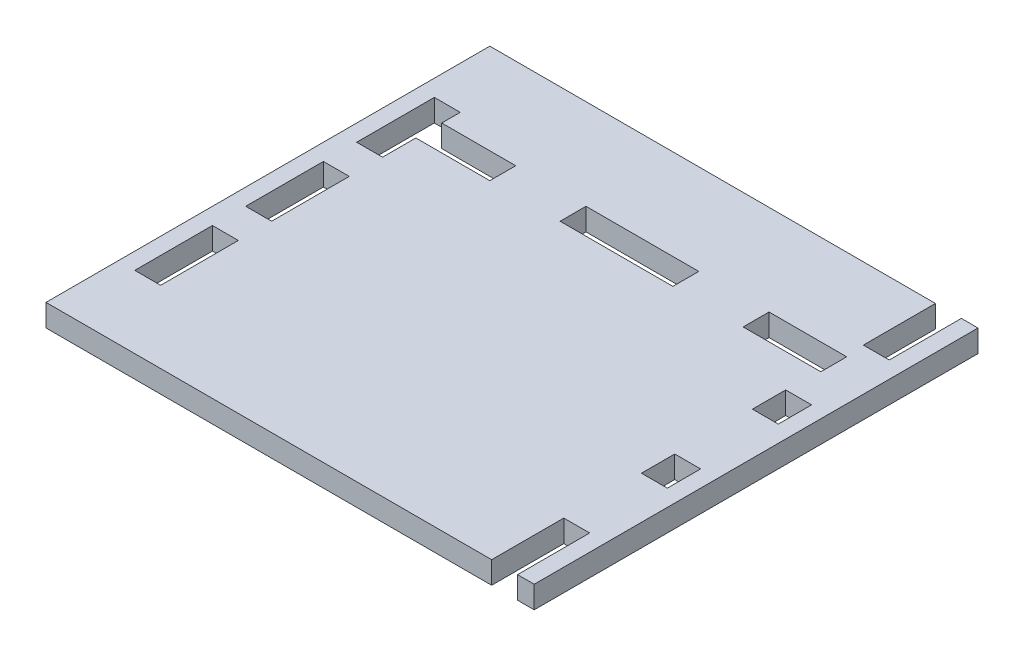
SolidWorks part; units mm, degrees
ref_plane "Спереди" through (0, 0, 0) normal (0, 0, 1) x (1, 0, 0)
ref_plane "Сверху" through (0, 0, 0) normal (0, 1, 0) x (1, 0, 0)
ref_plane "Справа" through (0, 0, 0) normal (1, 0, 0) x (0, 0, -1)
sketch "Эскиз1" plane through (0, 0, 0) normal (0, 1, 0) x (1, 0, 0)
  line L0 (-30.75, 10.7991) -> (-27.25, 10.7991)
  line L1 (33, -24.4509) -> (-33, -24.4509) construction
  line L2 (33, -24.4509) -> (33, 35.5491) construction
  line L3 (33, 35.5491) -> (-33, 35.5491) construction
  line L4 (-33, -24.4509) -> (-33, 35.5491) construction
  line L5 (-30.75, 25.7991) -> (-27.25, 25.7991)
  line L6 (-30.75, 25.7991) -> (-30.75, 15.2991)
  line L7 (-30.75, 15.2991) -> (-27.25, 15.2991)
  line L8 (-27.25, 25.7991) -> (-27.25, 23.2991)
  line L9 (-30.75, 10.7991) -> (-30.75, 0.2991)
  line L10 (-30.75, 0.2991) -> (-27.25, 0.2991)
  line L11 (-27.25, 10.7991) -> (-27.25, 0.2991)
  line L12 (-30.75, -4.2009) -> (-27.25, -4.2009)
  line L13 (-30.75, -4.2009) -> (-30.75, -14.7009)
  line L14 (-30.75, -14.7009) -> (-27.25, -14.7009)
  line L15 (-27.25, -4.2009) -> (-27.25, -14.7009)
  line L16 (0, -24.4509) -> (0, 0) construction
  line L17 (-27.25, 19.7991) -> (-27.25, 15.2991)
  line L21 (0, 0) -> (14.682, 0) construction
  line L22 (30.75, -14.7009) -> (27.25, -14.7009)
  line L23 (27.25, 10.7991) -> (30.75, 10.7991)
  line L24 (30.75, -4.2009) -> (27.25, -4.2009)
  line L25 (30.75, 10.7991) -> (30.75, 15.2991)
  line L26 (30.75, 0.2991) -> (27.25, 0.2991)
  line L27 (30.75, 15.2991) -> (27.25, 15.2991)
  line L28 (27.25, 15.2991) -> (27.25, 10.7991)
  line L29 (27.25, 25.7991) -> (27.25, 35.5491)
  line L34 (27.25, 35.5491) -> (30.75, 35.5491)
  line L35 (30.75, 35.5491) -> (30.75, 25.7991)
  line L36 (30.75, 25.7991) -> (27.25, 25.7991)
  line L37 (30.75, -4.2009) -> (30.75, 0.2991)
  line L39 (-27.25, 23.2991) -> (-17.25, 23.2991)
  line L41 (-27.25, 19.7991) -> (-17.25, 19.7991)
  line L42 (-17.25, 23.2991) -> (-17.25, 19.7991)
  line L43 (-7.75, 23.2991) -> (7.5, 23.2991)
  line L44 (-7.75, 23.2991) -> (-7.75, 19.7991)
  line L45 (-7.75, 19.7991) -> (7.5, 19.7991)
  line L46 (27.25, 0.2991) -> (27.25, -4.2009)
  line L47 (30.75, -14.7009) -> (30.75, -24.4509)
  line L48 (30.75, -24.4509) -> (27.25, -24.4509)
  line L49 (27.25, -24.4509) -> (27.25, -14.7009)
  line L50 (7.5, 23.2991) -> (7.5, 19.7991)
  line L51 (17, 23.2991) -> (27.5, 23.2991)
  line L52 (17, 23.2991) -> (17, 19.7991)
  line L53 (17, 19.7991) -> (27.5, 19.7991)
  line L54 (27.5, 23.2991) -> (27.5, 19.7991)
  dimension "D1" = 60
  dimension "D2" = 10.5
  dimension "D3" = 3.5
  dimension "D4" = 10.5
  dimension "D5" = 9.75
  dimension "D7" = 4.5
  dimension "D8" = 2.25
  dimension "D9" = 11
  dimension "D14" = 66
  dimension "D15" = 15.25
  dimension "D16" = 9.5
  dimension "D17" = 10
  dimension "D6" = 3
sketch "Эскиз3" plane through (0, 0, 0) normal (0, 1, 0) x (1, 0, 0)
  line L0 (-33, 35.5491) -> (-33, -24.4509)
  line L1 (-33, -24.4509) -> (33, -24.4509)
  line L2 (33, -24.4509) -> (33, 35.5491)
  line L3 (33, 35.5491) -> (-33, 35.5491)
extrude "Бобышка-Вытянуть1" add sketch "Эскиз3" along normal blind 3
extrude "Вырез-Вытянуть1" cut sketch "Эскиз1" along normal through all
